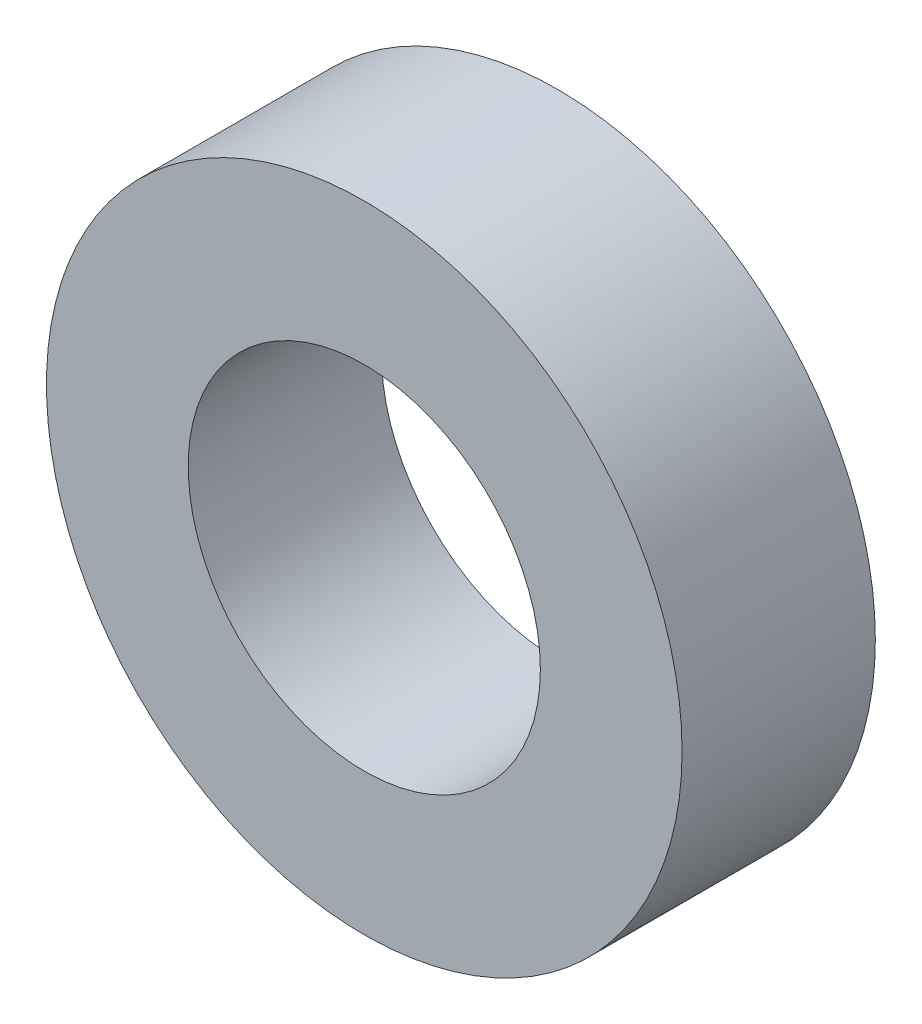
SolidWorks part; units mm, degrees
material "PET"
ref_plane "Piano frontale" through (0, 0, 0) normal (0, 0, 1) x (1, 0, 0)
ref_plane "Piano superiore" through (0, 0, 0) normal (0, 1, 0) x (1, 0, 0)
ref_plane "Piano destro" through (0, 0, 0) normal (1, 0, 0) x (0, 0, -1)
sketch "Schizzo1" plane through (0, 0, 0) normal (0, 0, 1) x (1, 0, 0)
  circle A0 centre (0, 0) radius 4.1
  circle A1 centre (0, 0) radius 7.4
  dimension "D1" = 8.2
  dimension "D2" = 14.8
extrude "Estrusione-Estrusione1" add sketch "Schizzo1" along normal blind 4.5
